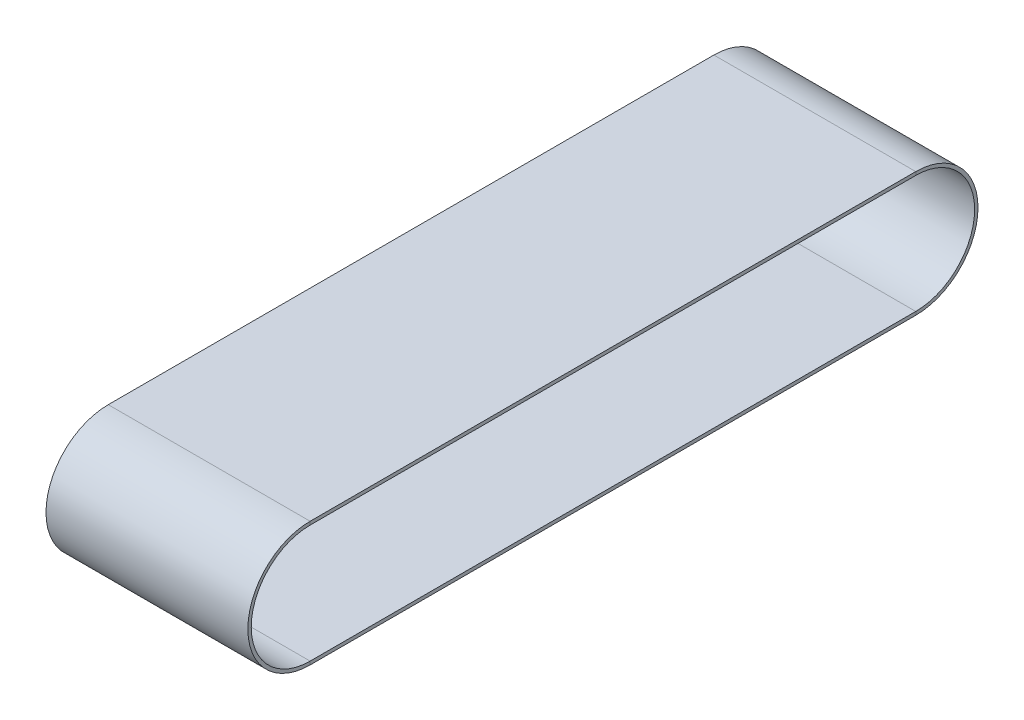
SolidWorks part; units mm, degrees
ref_plane "Front Plane" through (0, 0, 0) normal (0, 0, 1) x (1, 0, 0)
ref_plane "Top Plane" through (0, 0, 0) normal (0, 1, 0) x (1, 0, 0)
ref_plane "Right Plane" through (0, 0, 0) normal (1, 0, 0) x (0, 0, -1)
sketch "Sketch1" plane through (0, 0, 0) normal (0, 0, 1) x (1, 0, 0)
  line L0 (-76.2, 44.45) -> (-76.2, 46.99)
  line L1 (-76.2, 44.45) -> (76.2, 44.45)
  line L2 (-76.2, 46.99) -> (76.2, 46.99)
  line L3 (76.2, 44.45) -> (76.2, 46.99)
  line L4 (-76.2, 44.45) -> (76.2, 46.99) construction
  line L5 (-76.2, 46.99) -> (76.2, 44.45) construction
  point P0 (0, 0)
  point P1 (0, 45.72)
  dimension "D1" = 44.45
  dimension "D2" = 152.4
  dimension "D3" = 2.54
sketch "Sketch2" plane through (0, 0, 0) normal (1, 0, 0) x (0, 0, -1)
  line L0 (0, 45.72) -> (457.2, 45.72)
  line L1 (0, 0) -> (457.2, 0) construction
  line L2 (0, -45.72) -> (457.2, -45.72)
  arc A0 (0, 45.72) -> (0, -45.72) centre (0, 0) ccw
  arc A1 (457.2, 45.72) -> (457.2, -45.72) centre (457.2, 0) cw
  dimension "D1" = 457.2
sweep "Sweep1" add profiles "Sketch1" path "Sketch2"
